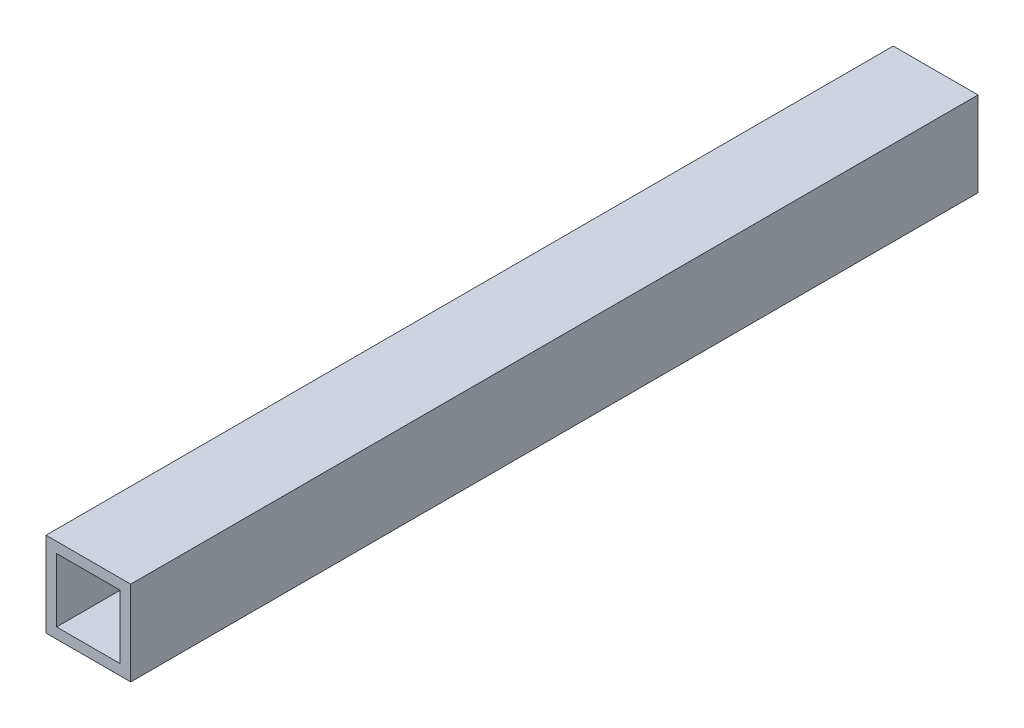
SolidWorks part; units mm, degrees
ref_plane "Plan de face" through (0, 0, 0) normal (0, 0, 1) x (1, 0, 0)
ref_plane "Plan de dessus" through (0, 0, 0) normal (0, 1, 0) x (1, 0, 0)
ref_plane "Plan de droite" through (0, 0, 0) normal (1, 0, 0) x (0, 0, -1)
sketch "Esquisse1" plane through (0, 0, 0) normal (0, 0, 1) x (1, 0, 0)
  line L0 (0, 20) -> (20, 0) construction
  line L1 (0, 0) -> (20, 0)
  line L2 (0, 0) -> (0, 20)
  line L3 (0, 20) -> (20, 20)
  line L4 (20, 0) -> (20, 20)
  line L6 (2.5, 17.5) -> (17.5, 17.5)
  line L7 (2.5, 17.5) -> (2.5, 2.5)
  line L8 (2.5, 2.5) -> (17.5, 2.5)
  line L9 (17.5, 17.5) -> (17.5, 2.5)
  line L10 (2.5, 17.5) -> (17.5, 2.5) construction
  line L11 (2.5, 2.5) -> (17.5, 17.5) construction
  point P5 (10, 10)
  dimension "D1" = 20
  dimension "D2" = 20
  dimension "D3" = 15
extrude "Boss.-Extru.1" add sketch "Esquisse1" along normal blind 200
